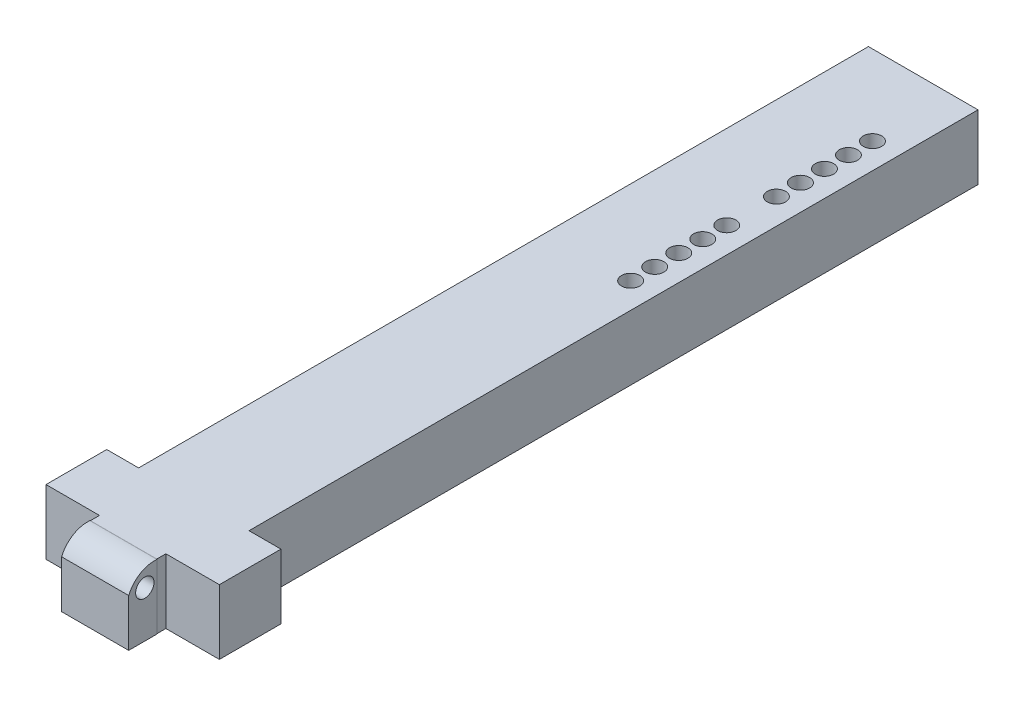
SolidWorks part; units mm, degrees
ref_plane "Front Plane" through (0, 0, 0) normal (0, 0, 1) x (1, 0, 0)
ref_plane "Top Plane" through (0, 0, 0) normal (0, 1, 0) x (1, 0, 0)
ref_plane "Right Plane" through (0, 0, 0) normal (1, 0, 0) x (0, 0, -1)
sketch "Sketch1" plane through (0, 0, 0) normal (0, 1, 0) x (1, 0, 0)
  line L1 (-10.15, 81.203) -> (10.15, 81.203)
  line L5 (16.06, -65.2544) -> (6.15, -65.2544)
  line L6 (16.06, -65.2544) -> (16.06, -53.8486)
  line L8 (6.15, -65.2544) -> (6.15, -66.9344)
  line L10 (-6.15, -66.9344) -> (-6.15, -65.2544)
  line L14 (-10.15, 81.203) -> (-10.15, -54.0044)
  line L15 (16.06, -53.8486) -> (10.15, -53.8486)
  line L16 (-16.06, -54.0044) -> (-16.06, -65.2544)
  line L17 (-6.15, -65.2544) -> (-16.06, -65.2544)
  line L18 (-6.15, -66.9344) -> (6.15, -66.9344)
  line L19 (10.15, 81.203) -> (10.15, -53.8486)
  line L20 (-10.15, -54.0044) -> (-16.06, -54.0044)
  circle A9 centre (5.4, 57.504) radius 1.7
  circle A10 centre (5.4, 30.504) radius 1.7
  circle A11 centre (5.4001, 53.054) radius 1.7
  circle A12 centre (5.4001, 26.054) radius 1.7
  circle A13 centre (5.4, 61.954) radius 1.7
  circle A14 centre (5.3999, 34.954) radius 1.7
  circle A15 centre (5.4, 48.604) radius 1.7
  circle A16 centre (5.4, 66.404) radius 1.7
  circle A17 centre (5.4, 21.604) radius 1.7
  circle A18 centre (5.4, 39.404) radius 1.7
  point P0 (0, 0)
  dimension "D1" = 3.4
  dimension "D2" = 3.4
  dimension "D3" = 27
  dimension "D4" = 6.15
  dimension "D5" = 5.91
  dimension "D6" = 4.75
  dimension "D7" = 4.45
  dimension "D8" = 4.45
  dimension "D9" = 4.45
  dimension "D10" = 4.45
  dimension "D11" = 20.3
  dimension "D12" = 5.91
  dimension "D13" = 4.75
  dimension "D14" = 4.75
  dimension "D15" = 6.15
  dimension "D16" = 1.68
  dimension "D17" = 23.6989
  dimension "D18" = 4.45
  dimension "D19" = 4.45
  dimension "D20" = 4.45
  dimension "D21" = 4.45
  dimension "D22" = 32.12
  dimension "D23" = 11.25
  dimension "D24" = 135.0516
extrude "Boss-Extrude1" add sketch "Sketch1" along normal blind 12
sketch "Sketch2" plane through (0, 0, 0) normal (1, 0, 0) x (0, 0, -1)
  line L3 (-72.2073, 5.9997) -> (-72.2073, 8.8097)
  line L9 (-72.2073, 0) -> (-72.2073, 5.9997)
  line L10 (-66.9773, 11.9997) -> (-66.9344, 12)
  line L11 (-66.9344, 12) -> (-66.9344, 0)
  line L12 (-66.9344, 0) -> (-72.2073, 0)
  circle A1 centre (-69.2173, 8.5797) radius 1.7
  arc A4 (-72.2073, 8.8097) -> (-66.9773, 11.9997) centre (-67.3984, 6.8078) cw
  dimension "D2" = 3.4
  dimension "D4" = 2.81
extrude "Boss-Extrude2" add sketch "Sketch2" along normal mid plane 12.425
